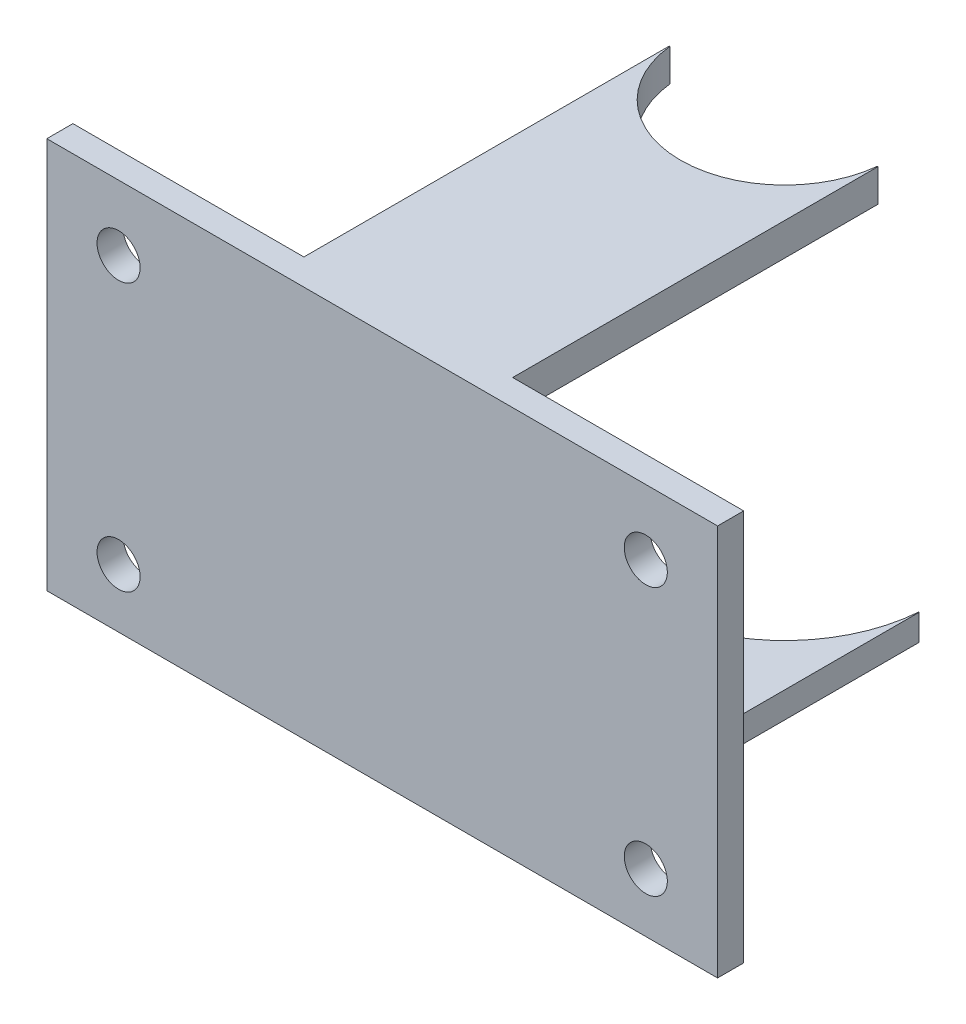
SolidWorks part; units mm, degrees
ref_plane "Front Plane" through (0, 0, 0) normal (0, 0, 1) x (1, 0, 0)
ref_plane "Top Plane" through (0, 0, 0) normal (0, 1, 0) x (1, 0, 0)
ref_plane "Right Plane" through (0, 0, 0) normal (1, 0, 0) x (0, 0, -1)
sketch "Sketch1" plane through (0, 0, 0) normal (0, 0, 1) x (1, 0, 0)
  line L1 (0, 0) -> (51.4, 0)
  line L2 (0, 0) -> (0, 30)
  line L3 (0, 30) -> (51.4, 30)
  line L4 (51.4, 0) -> (51.4, 30)
  dimension "D1" = 51.4
  dimension "D2" = 30
extrude "Boss-Extrude1" add sketch "Sketch1" along normal blind 2
sketch "Sketch2" plane through (0, 0, 0) normal (0, 0, -1) x (-1, 0, 0)
  line L0 (-51.4, 0) -> (-51.4, 30) construction
  line L1 (-5.5, 25) -> (-45.9, 25) construction
  line L2 (-5.5, 25) -> (-5.5, 4.5) construction
  line L3 (-5.5, 4.5) -> (-45.9, 4.5) construction
  line L4 (-45.9, 25) -> (-45.9, 4.5) construction
  line L5 (-5.5, 25) -> (-45.9, 4.5) construction
  line L6 (-5.5, 4.5) -> (-45.9, 25) construction
  line L7 (0, 30) -> (0, 0) construction
  line L8 (-51.4, 30) -> (0, 30) construction
  circle A0 centre (-45.9, 25) radius 1.65
  circle A1 centre (-5.5, 25) radius 1.65
  circle A2 centre (-5.5, 4.5) radius 1.65
  circle A3 centre (-45.9, 4.5) radius 1.65
  point P9 (-25.7, 14.75)
  point P13 (0, 0)
  dimension "D1" = 3.3
  dimension "D2" = 5.5
  dimension "D3" = 5.5
  dimension "D4" = 5
  dimension "D5" = 20.5
extrude "Cut-Extrude1" cut sketch "Sketch2" against normal blind 15
sketch "Sketch3" plane through (0, 0, 0) normal (0, 0, -1) x (-1, 0, 0)
  line L5 (-25.7, 30) -> (-25.7, 0) construction
  line L6 (-51.4, 30) -> (0, 30) construction
  line L12 (0, 0) -> (-51.4, 0) construction
  line L14 (-33.7, 27.5) -> (-17.7, 27.5)
  line L15 (-33.7, 27.5) -> (-33.7, 30)
  line L16 (-33.7, 30) -> (-17.7, 30)
  line L17 (-17.7, 27.5) -> (-17.7, 30)
  line L18 (-33.7, 27.5) -> (-17.7, 30) construction
  line L19 (-33.7, 30) -> (-17.7, 27.5) construction
  line L20 (-36.85, 2) -> (-14.55, 2)
  line L21 (-36.85, 2) -> (-36.85, 0)
  line L22 (-36.85, 0) -> (-14.55, 0)
  line L23 (-14.55, 2) -> (-14.55, 0)
  line L24 (-36.85, 2) -> (-14.55, 0) construction
  line L25 (-36.85, 0) -> (-14.55, 2) construction
  point P10 (-25.7, 28.75)
  point P15 (-25.7, 1)
  dimension "D1" = 16
  dimension "D2" = 2.5
  dimension "D3" = 22.3
  dimension "D4" = 2
extrude "Boss-Extrude2" add sketch "Sketch3" along normal blind 28
sketch "Sketch4" plane through (0, 30, 0) normal (0, 1, 0) x (1, 0, 0)
  line L0 (51.4, 0) -> (33.7, 0) construction
  line L1 (25.7, 28.85) -> (25.7, -2) construction
  line L3 (51.4, -2) -> (0, -2) construction
  circle A0 centre (25.7, 28.85) radius 8
  dimension "D1" = 16
  dimension "D2" = 28.85
extrude "Cut-Extrude3" cut sketch "Sketch4" against normal blind 10
sketch "Sketch6" plane through (0, 2, 0) normal (0, 1, 0) x (1, 0, 0)
  circle A0 centre (25.7, 28.85) radius 11.15
  dimension "D1" = 22.3
extrude "Cut-Extrude4" cut sketch "Sketch6" against normal blind 10
